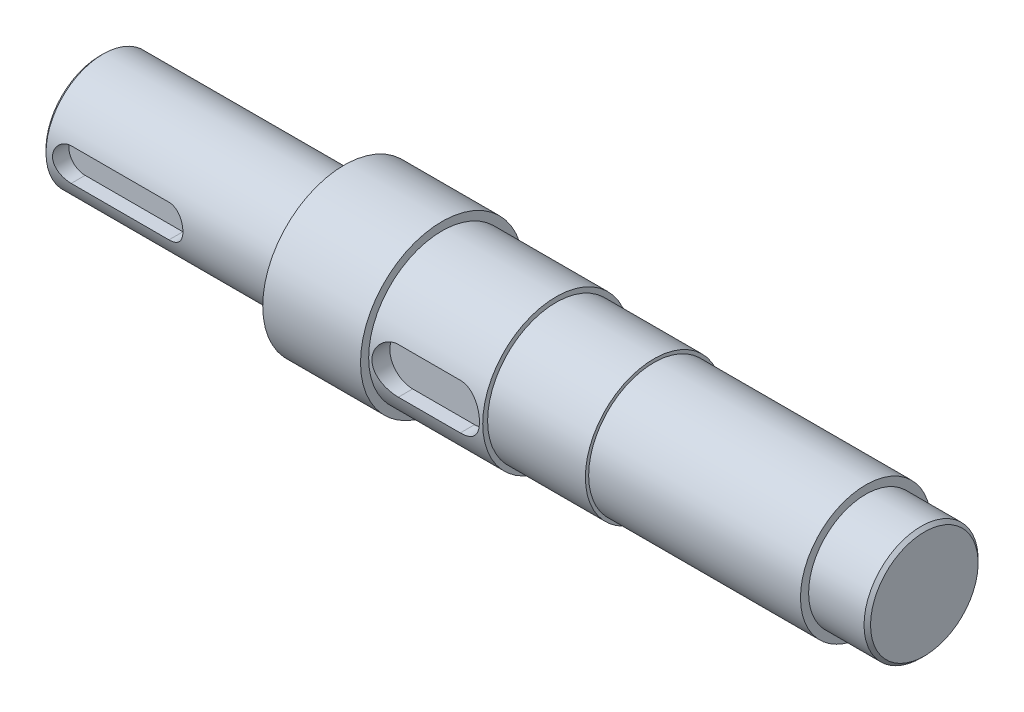
SolidWorks part; units mm, degrees
other "细节项目14"
other "细节项目15"
other "细节项目16"
material "45"
ref_plane "前视基准面" through (0, 0, 0) normal (0, 0, 1) x (1, 0, 0)
ref_plane "上视基准面" through (0, 0, 0) normal (0, 1, 0) x (1, 0, 0)
ref_plane "右视基准面" through (0, 0, 0) normal (1, 0, 0) x (0, 0, -1)
sketch "草图1" plane through (0, 0, 0) normal (0, 0, 1) x (1, 0, 0)
  line L0 (0, 0) -> (50000, 0) construction
  line L1 (0, 0) -> (0, -50000) construction
  line L2 (0, 0) -> (0, 17.5)
  line L3 (0, 17.5) -> (45, 17.5)
  line L4 (75, 17.5) -> (75, 25)
  line L5 (75, 25) -> (105, 25)
  line L6 (235, 20) -> (235, 17.5)
  line L7 (235, 17.5) -> (253, 17.5)
  line L8 (253, 17.5) -> (253, 0)
  line L9 (253, 0) -> (0, 0)
  line L10 (105, 25) -> (105, 22.5)
  line L11 (105, 22.5) -> (140, 22.5)
  line L12 (140, 22.5) -> (140, 21)
  line L13 (140, 21) -> (170, 21)
  line L14 (170, 21) -> (170, 20)
  line L15 (45, 17.5) -> (75, 17.5)
  line L16 (170, 20) -> (235, 20)
  dimension "D1" = 35
  dimension "D2" = 75
  dimension "D3" = 253
  dimension "D4" = 50
  dimension "D5" = 35
  dimension "D6" = 18
  dimension "D7" = 30
  dimension "D8" = 45
  dimension "D9" = 35
  dimension "D10" = 40
  dimension "D11" = 42
  dimension "D12" = 30
revolve "旋转1" add sketch "草图1" angle 360 about L0
cosmetic thread "装饰螺纹线1" parameters "D1"=30, "D2"=40.5
sketch "草图2" plane through (0, 0, 0) normal (-1, 0, 0) x (0, 0, 1)
  circle A0 centre (0, 0) radius 3
  dimension "D1" = 6
hole_wizard "M6 螺纹孔1" positions "3D草图1" profile "草图3" tap size "M6" standard "Gb"
sketch3d "3D草图1"
  circle A0 centre (0, 0, 0) radius 3 construction
  point P0 (0, 0, 0)
  point P6 (-3, 0, 0)
sketch "草图3" plane through (0, 0, 0) normal (0, 1, 0) x (0, 0, 1)
  line L0 (0, 0) -> (0, 18.5022)
  line L1 (0, 18.5022) -> (2.5, 17)
  line L2 (2.5, 17) -> (2.5, 0)
  line L5 (2.5, 0) -> (0, 0)
  line L10 (0, 18.5022) -> (-2.5, 17) construction
  line L11 (0, -6.35) -> (0, 107.95) construction
  dimension "螺纹孔钻头直径" = 5
  dimension "螺纹孔钻头深度" = 17
  dimension "导头角度" = 118
cosmetic thread "孔螺蚊线1" parameters "D1"=12, "D2"=6
ref_plane "基准面1" through (0, 0, 17) normal (0, 0, 1) x (1, 0, 0)
sketch "草图4" plane through (0, 0, 17) normal (0, 0, 1) x (1, 0, 0)
  line L0 (0, 0) -> (-50000, 0) construction
  line L1 (113, 0) -> (132, 0) construction
  line L2 (113, 7) -> (132, 7)
  line L3 (113, -7) -> (132, -7)
  line L7 (105, -22.5) -> (105, 22.5) construction
  arc A0 (113, 7) -> (113, -7) centre (113, 0) ccw
  arc A1 (132, -7) -> (132, 7) centre (132, 0) ccw
  point P5 (122.5, 0)
  dimension "D1" = 14
  dimension "D3" = 8
  dimension "D4" = 19
extrude "切除-拉伸1" cut sketch "草图4" along normal blind 10
ref_plane "基准面2" through (0, 0, 12.5) normal (0, 0, 1) x (1, 0, 0)
sketch "草图5" plane through (0, 0, 12.5) normal (0, 0, 1) x (1, 0, 0)
  line L0 (0, 0) -> (-50000, 0) construction
  line L1 (8, 0) -> (38, 0) construction
  line L2 (8, 5) -> (38, 5)
  line L3 (8, -5) -> (38, -5)
  line L4 (0, 17.5) -> (0, -17.5) construction
  arc A0 (8, 5) -> (8, -5) centre (8, 0) ccw
  arc A1 (38, -5) -> (38, 5) centre (38, 0) ccw
  point P5 (23, 0)
  dimension "D1" = 8
  dimension "D2" = 30
  dimension "D3" = 10
extrude "切除-拉伸2" cut sketch "草图5" along normal blind 10
chamfer "倒角1" distance 1 angle 45 2 edges at (253, 0, 17.5) (0, 0, 17.5)
